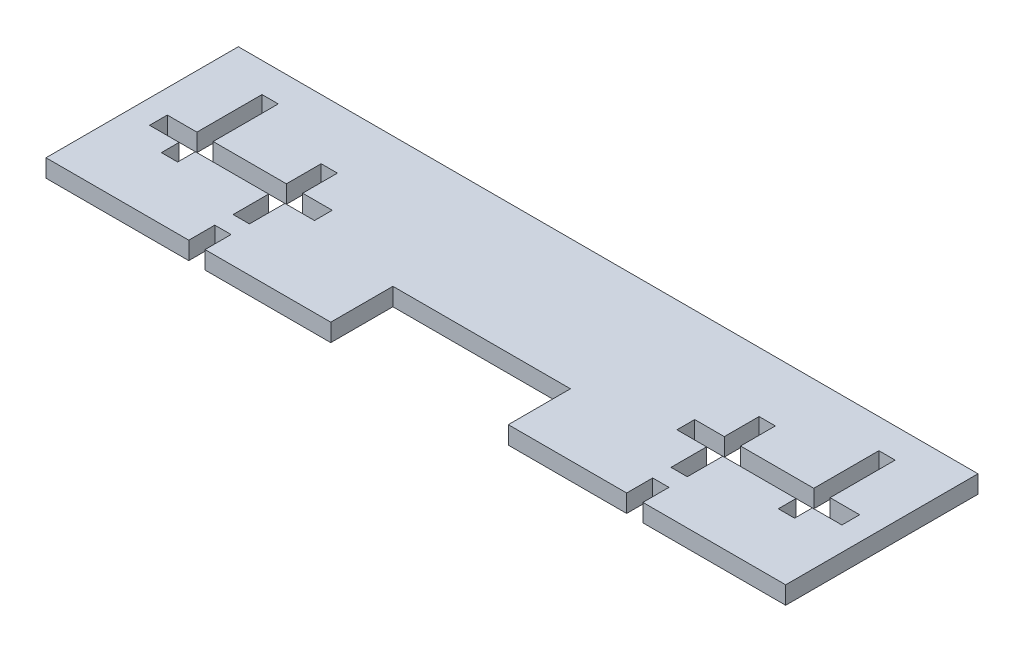
SolidWorks part; units mm, degrees
ref_plane "Front" through (0, 0, 0) normal (0, 0, 1) x (1, 0, 0)
ref_plane "Top" through (0, 0, 0) normal (0, 1, 0) x (1, 0, 0)
ref_plane "Right" through (0, 0, 0) normal (1, 0, 0) x (0, 0, -1)
sketch "Sketch1" plane through (0, 0, 0) normal (0, 1, 0) x (1, 0, 0)
  line L1 (0, 0) -> (250, 0)
  line L2 (0, 0) -> (0, 65)
  line L3 (0, 65) -> (250, 65)
  line L4 (250, 0) -> (250, 65)
  point P4 (0, 0)
  dimension "D1" = 65
  dimension "D2" = 250
extrude "Boss-Extrude1" add sketch "Sketch1" along normal blind 6
sketch "Sketch2" plane through (0, 6, 0) normal (0, 1, 0) x (1, 0, 0)
  line L0 (125, 65) -> (125, 0) construction
  line L1 (18, 55) -> (23.5, 55)
  line L2 (18, 55) -> (18, 21)
  line L3 (18, 21) -> (23.5, 21)
  line L4 (23.5, 55) -> (23.5, 21)
  line L5 (48.25, 44.75) -> (53.75, 44.75)
  line L6 (48.25, 44.75) -> (48.25, -2.75)
  line L7 (48.25, -2.75) -> (53.75, -2.75)
  line L8 (53.75, 44.75) -> (53.75, -2.75)
  line L9 (250, 65) -> (0, 65) construction
  line L10 (0, 0) -> (250, 0) construction
  line L11 (0, 32.5) -> (125, 32.5) construction
  line L12 (0, 65) -> (0, 0) construction
  line L13 (196.25, 44.75) -> (196.25, -2.75)
  line L14 (201.75, -2.75) -> (196.25, -2.75)
  line L15 (201.75, 44.75) -> (201.75, -2.75)
  line L16 (201.75, 44.75) -> (196.25, 44.75)
  line L17 (226.5, 55) -> (226.5, 21)
  line L18 (232, 21) -> (226.5, 21)
  line L19 (232, 55) -> (232, 21)
  line L20 (232, 55) -> (226.5, 55)
  point P14 (18, 38)
  dimension "D1" = 107
  dimension "D2" = 24.75
  dimension "D3" = 47.5
  dimension "D4" = 34
  dimension "D5" = 5.5
  dimension "D6" = 10.25
  dimension "D7" = 10
extrude "Cut-Extrude1" cut sketch "Sketch2" against normal through all
sketch "Sketch3" plane through (0, 6, 0) normal (0, 1, 0) x (1, 0, 0)
  line L0 (0, 0) -> (48.25, 0) construction
  line L1 (156.25, 0) -> (96.25, 0)
  line L2 (156.25, 0) -> (156.25, 21)
  line L3 (156.25, 21) -> (96.25, 21)
  line L4 (96.25, 0) -> (96.25, 21)
  line L5 (196.25, 44.75) -> (196.25, 0) construction
  line L6 (18, 21) -> (23.5, 21) construction
  dimension "D1" = 40
  dimension "D2" = 60
extrude "Cut-Extrude2" cut sketch "Sketch3" against normal through all
sketch "Sketch4" plane through (0, 6, 0) normal (0, 1, 0) x (1, 0, 0)
  line L1 (8, 33) -> (63.75, 33)
  line L2 (8, 33) -> (8, 27)
  line L3 (8, 27) -> (63.75, 27)
  line L4 (63.75, 33) -> (63.75, 27)
  line L6 (18, 21) -> (23.5, 21) construction
  line L7 (53.75, 0) -> (53.75, 44.75) construction
  line L8 (18, 55) -> (18, 21) construction
  dimension "D1" = 6
  dimension "D2" = 6
  dimension "D3" = 10
  dimension "D4" = 10
extrude "Cut-Extrude3" cut sketch "Sketch4" against normal through all
sketch "Sketch5" plane through (0, 6, 0) normal (0, 1, 0) x (1, 0, 0)
  line L0 (48.25, 27) -> (48.25, 0) construction
  line L1 (48.25, 15) -> (53.75, 15)
  line L2 (48.25, 15) -> (48.25, 8.8)
  line L3 (48.25, 8.8) -> (53.75, 8.8)
  line L4 (53.75, 15) -> (53.75, 8.8)
  line L5 (53.75, 0) -> (53.75, 27) construction
  line L6 (53.75, 27) -> (63.75, 27) construction
  dimension "D1" = 6.2
  dimension "D2" = 12
extrude "Boss-Extrude2" add sketch "Sketch5" against normal blind 6
ref_plane "Plane1" through (125, 0, 0) normal (1, 0, 0) x (0, 0, -1)
mirror "Mirror1" about plane through (125, 0, 0) normal (1, 0, 0) of "Cut-Extrude3", "Boss-Extrude2"
